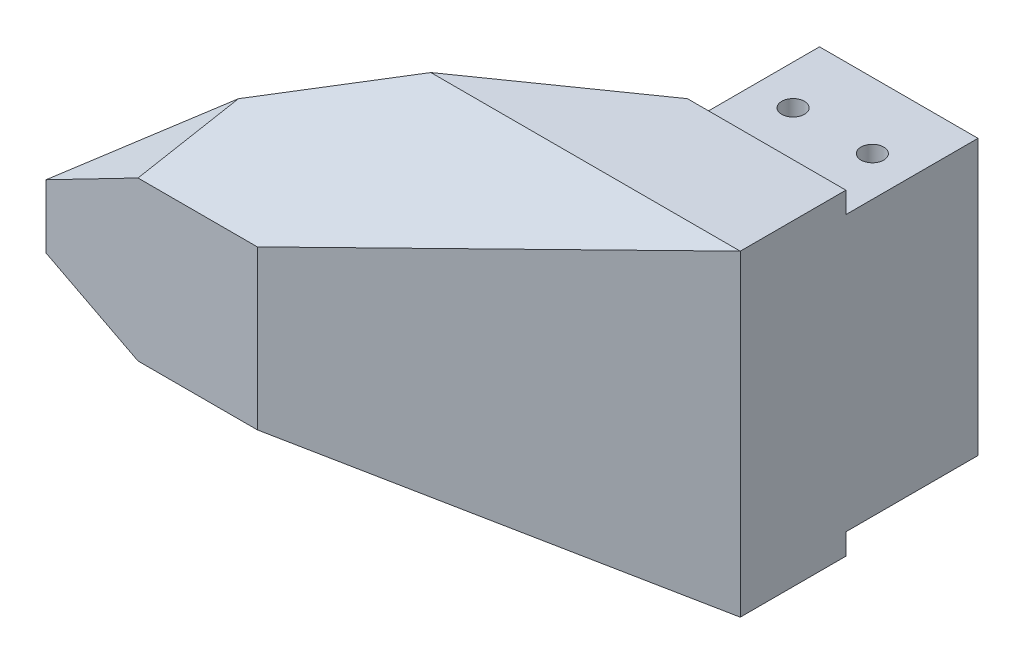
SolidWorks part; units mm, degrees
ref_plane "前视基准面" through (0, 0, 0) normal (0, 0, 1) x (1, 0, 0)
ref_plane "上视基准面" through (0, 0, 0) normal (0, 1, 0) x (1, 0, 0)
ref_plane "右视基准面" through (0, 0, 0) normal (1, 0, 0) x (0, 0, -1)
sketch "草图2" plane through (0, 0, 0) normal (0, 1, 0) x (1, 0, 0)
  line L0 (0, 0) -> (71.4074, 50)
  line L2 (101.4074, 30) -> (40, 0)
  line L3 (40, 0) -> (0, 0)
  line L4 (71.4074, 50) -> (71.4074, 75)
  line L5 (71.4074, 75) -> (101.4074, 75)
  line L6 (101.4074, 75) -> (101.4074, 30)
  dimension "D1" = 50
  dimension "D2" = 30
  dimension "D3" = 145
  dimension "D4" = 40
  dimension "D5" = 30
  dimension "D6" = 25
extrude "凸台-拉伸1" add sketch "草图2" along normal blind 30
sketch "草图4" plane through (101.4074, 0, 0) normal (1, 0, 0) x (0, 0, -1)
  line L0 (0, 30) -> (30, 45)
  line L1 (30, 45) -> (75, 45)
  line L2 (75, 45) -> (75, 30)
  line L3 (75, 30) -> (0, 30)
  line L4 (0, 0) -> (75, 0)
  line L5 (75, 0) -> (75, -15)
  line L6 (75, -15) -> (30, -15)
  line L7 (30, -15) -> (0, 0)
  line L8 (30, 30) -> (30, 0) construction
  dimension "D1" = 15
extrude "凸台-拉伸2" add sketch "草图4" against normal through all
sketch "草图5" plane through (0, -15, 0) normal (0, -1, 0) x (1, 0, 0)
  line L0 (40, 0) -> (101.4074, 0) construction
  line L1 (40, 0) -> (101.4074, -30) construction
  line L2 (101.4074, 0) -> (101.4074, -30) construction
  line L3 (0, 0) -> (0, -75) construction
  line L4 (0, -75) -> (71.4074, -75) construction
  line L5 (71.4074, -75) -> (71.4074, -50) construction
  line L6 (71.4074, -50) -> (0, 0) construction
  line L7 (40, 0) -> (101.4074, 0)
  line L8 (40, 0) -> (101.4074, -30)
  line L9 (101.4074, 0) -> (101.4074, -30)
  line L10 (0, 0) -> (0, -75)
  line L11 (0, -75) -> (71.4074, -75)
  line L12 (71.4074, -75) -> (71.4074, -50)
  line L13 (71.4074, -50) -> (0, 0)
extrude "切除-拉伸2" cut sketch "草图5" against normal through all
sketch "草图6" plane through (0, 0, 0) normal (-0.5736, 0, -0.8192) x (-0.8192, 0, 0.5736)
  line L0 (0, 21) -> (-26.1517, 37.5)
  line L1 (0, 30) -> (0, 0) construction
  line L2 (0, 30) -> (-52.3034, 45) construction
  line L3 (-26.1517, 37.5) -> (0, 30)
  line L4 (0, 30) -> (0, 21)
  line L5 (0, 0) -> (-26.1517, -7.5)
  line L6 (-52.3034, -15) -> (0, 0) construction
  line L7 (-26.1517, -7.5) -> (0, 9)
  line L8 (0, 9) -> (0, 0)
  dimension "D1" = 9
extrude "切除-拉伸3" cut sketch "草图6" against normal through all
sketch "草图10" plane through (0, -15, 0) normal (0, -1, 0) x (1, 0, 0)
  line L1 (101.4074, -75) -> (71.4074, -75)
  line L2 (101.4074, -75) -> (101.4074, -50)
  line L3 (101.4074, -50) -> (71.4074, -50)
  line L4 (71.4074, -75) -> (71.4074, -50)
extrude "切除-拉伸6" cut sketch "草图10" against normal blind 4
sketch "草图11" plane through (0, 45, 0) normal (0, 1, 0) x (1, 0, 0)
  line L1 (101.4074, 75) -> (71.4074, 75)
  line L2 (101.4074, 75) -> (101.4074, 50)
  line L3 (101.4074, 50) -> (71.4074, 50)
  line L4 (71.4074, 75) -> (71.4074, 50)
extrude "切除-拉伸7" cut sketch "草图11" against normal blind 4
sketch "草图13" plane through (0, 41, 0) normal (0, 1, 0) x (1, 0, 0)
  line L0 (71.4074, 75) -> (71.4074, 50) construction
  line L1 (101.4074, 75) -> (71.4074, 75) construction
  circle A0 centre (78.9074, 62.5) radius 2.15
  circle A1 centre (93.9074, 62.5) radius 2.15
  point P6 (71.4074, 62.5)
  dimension "D3" = 4.3
  dimension "D1" = 15
  dimension "D2" = 7.5
extrude "切除-拉伸8" cut sketch "草图13" against normal through all
sketch "草图14" plane through (0, 0, -75) normal (0, 0, -1) x (-1, 0, 0)
  line L0 (-101.4074, 41) -> (-101.4074, -11) construction
  line L1 (-71.4074, -11) -> (-101.4074, -11) construction
  circle A0 centre (-86.4074, 15) radius 5
  point P4 (-101.4074, 15)
  point P7 (-86.4074, -11)
  dimension "D1" = 10
extrude "切除-拉伸9" cut sketch "草图14" against normal blind 40
